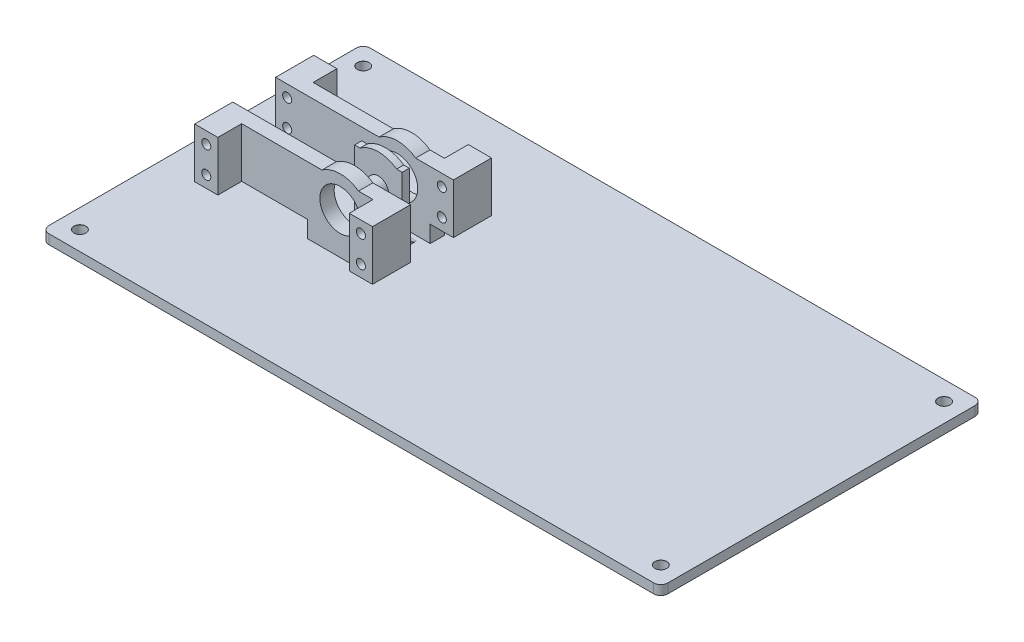
SolidWorks part; units mm, degrees
ref_plane "前视基准面" through (0, 0, 0) normal (0, 0, 1) x (1, 0, 0)
ref_plane "上视基准面" through (0, 0, 0) normal (0, 1, 0) x (1, 0, 0)
ref_plane "右视基准面" through (0, 0, 0) normal (1, 0, 0) x (0, 0, -1)
other "Configuration Table"
sketch "草图1" plane through (0, 0, 0) normal (0, 1, 0) x (1, 0, 0)
  line L1 (-130, -67.5) -> (130, -67.5)
  line L2 (-130, -67.5) -> (-130, 67.5)
  line L3 (-130, 67.5) -> (130, 67.5)
  line L4 (130, -67.5) -> (130, 67.5)
  line L5 (-130, -67.5) -> (130, 67.5) construction
  line L6 (-130, 67.5) -> (130, -67.5) construction
  point P0 (0, 0)
  dimension "D1" = 260
  dimension "D2" = 135
extrude "凸台-拉伸1" add sketch "草图1" along normal blind 4
sketch "草图2" plane through (0, 4, 0) normal (0, 1, 0) x (1, 0, 0)
  line L0 (-130, 0) -> (130, 0) construction
  line L1 (-130, 67.5) -> (-130, -67.5) construction
  line L2 (130, -67.5) -> (130, 67.5) construction
  line L3 (0, 67.5) -> (0, -67.5) construction
  line L4 (130, 67.5) -> (-130, 67.5) construction
  line L5 (-130, -67.5) -> (130, -67.5) construction
  point P0 (-122, 59.5)
  point P13 (-122, -59.5)
  point P14 (122, -59.5)
  point P15 (122, 59.5)
  dimension "D1" = 8
  dimension "D2" = 8
hole_wizard "Ø5.0 (5) 直径孔1" positions "草图2" profile "草图3" hole size "Ø5.0" standard "GB" end condition through all
sketch "草图3" plane through (-122, 4, -59.5) normal (1, 0, 0) x (0, 0, 1)
  line L0 (0, 0) -> (0, 4)
  line L1 (0, 4) -> (2.5, 4)
  line L2 (2.5, 4) -> (2.5, 0.025)
  line L3 (2.5, 0.025) -> (2.525, 0)
  line L5 (2.525, 0) -> (0, 0)
  line L6 (-2.5, 0.025) -> (-2.525, 0) construction
  line L11 (0, -6.35) -> (0, 107.95) construction
  dimension "通孔孔直径" = 5
  dimension "通孔孔深度" = 4
  dimension "近端锥形沉头孔直径" = 5.05
  dimension "近端锥形沉头孔角度" = 90
fillet "圆角1" radius 3 4 edges at (130, 2, -67.5) (130, 2, 67.5) (-130, 2, 67.5) (-130, 2, -67.5)
sketch "草图4" plane through (0, 0, 0) normal (0, 0, 1) x (1, 0, 0)
  line L1 (-70.9471, 4) -> (-43.3499, 4)
  line L3 (-98.5444, 32.0133) -> (-64.8208, 32.0133)
  line L4 (-43.3499, 4) -> (-43.3499, 11.0257)
  line L5 (-70.9471, 32.0133) -> (-70.9471, 4) construction
  line L6 (-98.5444, 11.0257) -> (-70.9471, 11.0257)
  line L7 (-57.1485, 32.0133) -> (-57.1485, 4) construction
  line L8 (-98.5444, 32.0133) -> (-108.2886, 32.0133)
  line L9 (-108.2886, 32.0133) -> (-108.2886, 11.0257)
  line L10 (-108.2886, 11.0257) -> (-98.5444, 11.0257)
  line L11 (-33.6057, 11.0257) -> (-43.3499, 11.0257)
  line L12 (-33.6057, 32.0133) -> (-33.6057, 11.0257)
  line L13 (-43.3499, 32.0133) -> (-33.6057, 32.0133)
  line L14 (-49.4762, 32.0133) -> (-43.3499, 32.0133)
  line L15 (-70.9471, 11.0257) -> (-70.9471, 4)
  arc A0 (-49.4762, 32.0133) -> (-64.8208, 32.0133) centre (-57.1485, 21.3151) ccw
extrude "凸台-拉伸2" add sketch "草图4" along normal mid plane 30
sketch "草图5" plane through (-108.2886, 0, 0) normal (-1, 0, 0) x (0, 0, 1)
  line L0 (0, 4) -> (0, 34.48) construction
  line L1 (15, 4) -> (-15, 4) construction
  line L2 (15, 34.48) -> (-15, 34.48) construction
  line L3 (-9, 34.48) -> (-9, 4)
  line L4 (9, 34.48) -> (9, 4)
  line L5 (-9, 4) -> (-4, 4)
  line L6 (-9, 34.48) -> (-4, 34.48)
  line L7 (-4, 34.48) -> (-4, 4)
  line L8 (-1, 34.48) -> (-1, 4)
  line L9 (-1, 34.48) -> (9, 34.48)
  line L10 (-1, 4) -> (9, 4)
  dimension "D1" = 9
  dimension "D2" = 5
  dimension "D3" = 3
extrude "切除-拉伸2" cut sketch "草图5" against normal through all
sketch "草图7" plane through (0, 32.0133, 0) normal (0, 1, 0) x (1, 0, 0)
  line L0 (-67.094, 4) -> (-67.094, 1)
  line L1 (-64.8208, 4) -> (-108.2886, 4) construction
  line L2 (-108.2886, 1) -> (-64.8208, 1) construction
  line L4 (-67.094, 4) -> (-108.2886, 4)
  line L5 (-108.2886, 4) -> (-108.2886, 1)
  line L6 (-108.2886, 1) -> (-67.094, 1)
extrude "切除-拉伸3" cut sketch "草图7" against normal up to surface (20.9875 mm away) up to face at (-89.6179, 11.0257, 12)
sketch "草图8" plane through (0, 32.0133, 0) normal (0, 1, 0) x (1, 0, 0)
  line L0 (-47.1483, 4) -> (-47.1483, 1)
  line L1 (-33.6057, 4) -> (-49.4762, 4) construction
  line L2 (-49.4762, 1) -> (-33.6057, 1) construction
  line L3 (-47.1483, 1) -> (-33.6057, 1)
  line L4 (-33.6057, 1) -> (-33.6057, 4)
  line L5 (-33.6057, 1) -> (-33.6057, 4) construction
  line L6 (-33.6057, 4) -> (-47.1483, 4)
extrude "切除-拉伸5" cut sketch "草图8" against normal up to surface (28.0133 mm away) up to face at (-57.1485, 4, -2.5)
sketch "草图9" plane through (0, 11.0257, 0) normal (0, 1, 0) x (1, 0, 0)
  line L0 (-67.094, 4) -> (-70.9471, 4)
  line L1 (-70.9471, 4) -> (-70.9471, 1)
  line L2 (-70.9471, 1) -> (-67.094, 1)
  line L3 (-67.094, 1) -> (-67.094, 4)
extrude "切除-拉伸6" cut sketch "草图9" against normal up to surface (7.0257 mm away) up to face at (-59.0477, 4, -2.5)
sketch "草图11" plane through (0, 0, 15) normal (0, 0, 1) x (1, 0, 0)
  line L0 (-43.3499, 11.0257) -> (-33.6057, 11.0257)
  line L1 (-33.6057, 11.0257) -> (-33.6057, 32.0133)
  line L2 (-33.6057, 32.0133) -> (-43.3499, 32.0133)
  line L3 (-33.6057, 32.0133) -> (-49.4762, 32.0133) construction
  line L4 (-43.3499, 32.0133) -> (-43.3499, 11.0257)
  line L5 (-70.9471, 11.0257) -> (-70.9471, 32.0133) construction
  line L6 (-64.8208, 32.0133) -> (-108.2886, 32.0133) construction
  line L7 (-108.2886, 32.0133) -> (-98.5444, 32.0133)
  line L8 (-108.2886, 11.0257) -> (-108.2886, 32.0133)
  line L9 (-98.5444, 11.0257) -> (-108.2886, 11.0257)
  line L10 (-98.5444, 32.0133) -> (-98.5444, 11.0257)
extrude "凸台-拉伸3" add sketch "草图11" along normal blind 10
sketch "草图12" plane through (0, 0, -15) normal (0, 0, -1) x (-1, 0, 0)
  line L0 (33.6057, 32.0133) -> (33.6057, 11.0257)
  line L1 (33.6057, 11.0257) -> (43.3499, 11.0257)
  line L2 (43.3499, 11.0257) -> (43.3499, 32.0133)
  line L3 (33.6057, 32.0133) -> (49.4762, 32.0133) construction
  line L4 (43.3499, 32.0133) -> (33.6057, 32.0133)
  line L5 (70.9471, 11.0257) -> (70.9471, 32.0133) construction
  line L6 (64.8208, 32.0133) -> (108.2886, 32.0133) construction
  line L7 (98.5444, 11.0257) -> (98.5444, 32.0133)
  line L8 (108.2886, 11.0257) -> (98.5444, 11.0257)
  line L9 (108.2886, 32.0133) -> (108.2886, 11.0257)
  line L10 (98.5444, 32.0133) -> (108.2886, 32.0133)
extrude "凸台-拉伸4" add sketch "草图12" along normal blind 10
sketch "草图13" plane through (0, 0, 25) normal (0, 0, 1) x (1, 0, 0)
  line L0 (-43.3499, 21.5195) -> (-33.6057, 21.5195) construction
  line L1 (-43.3499, 32.0133) -> (-43.3499, 11.0257) construction
  line L2 (-33.6057, 11.0257) -> (-33.6057, 32.0133) construction
  line L3 (-38.4778, 11.0257) -> (-38.4778, 32.0133) construction
  line L4 (-43.3499, 11.0257) -> (-33.6057, 11.0257) construction
  line L5 (-33.6057, 32.0133) -> (-43.3499, 32.0133) construction
  line L6 (-70.9471, 11.0257) -> (-70.9471, 32.0133) construction
  line L7 (-64.8208, 32.0133) -> (-98.5444, 32.0133) construction
  circle A0 centre (-38.4778, 27.075) radius 1.9077
  circle A1 centre (-38.4778, 15.9639) radius 1.9077
  circle A2 centre (-103.4165, 15.9639) radius 1.9077
  circle A3 centre (-103.4165, 27.075) radius 1.9077
extrude "切除-拉伸7" cut sketch "草图13" against normal through all
sketch "草图15" plane through (0, 0, 15) normal (0, 0, 1) x (1, 0, 0)
  line L0 (-57.1485, 4) -> (-57.1485, 34.48) construction
  line L1 (-70.9471, 4) -> (-43.3499, 4) construction
  arc A0 (-49.4762, 32.0133) -> (-64.8208, 32.0133) centre (-57.1485, 21.3151) ccw construction
  circle A1 centre (-57.1485, 21.3151) radius 8.5468
extrude "切除-拉伸8" cut sketch "草图15" against normal blind 10
mirror "镜向3" about plane through (0, 0, 0) normal (0, 0, 1) of "切除-拉伸8"
sketch "草图16" plane through (0, 0, -1) normal (0, 0, 1) x (1, 0, 0)
  circle A0 centre (-57.1485, 21.3151) radius 4.3798
  arc A1 (-49.4762, 32.0133) -> (-64.8208, 32.0133) centre (-57.1485, 21.3151) ccw construction
extrude "凸台-拉伸5" add sketch "草图16" along normal blind 5 and the other way blind 5
fillet "圆角2" radius 3 2 edges at (-57.1212, 4, -1) (-57.1212, 4, -4)
